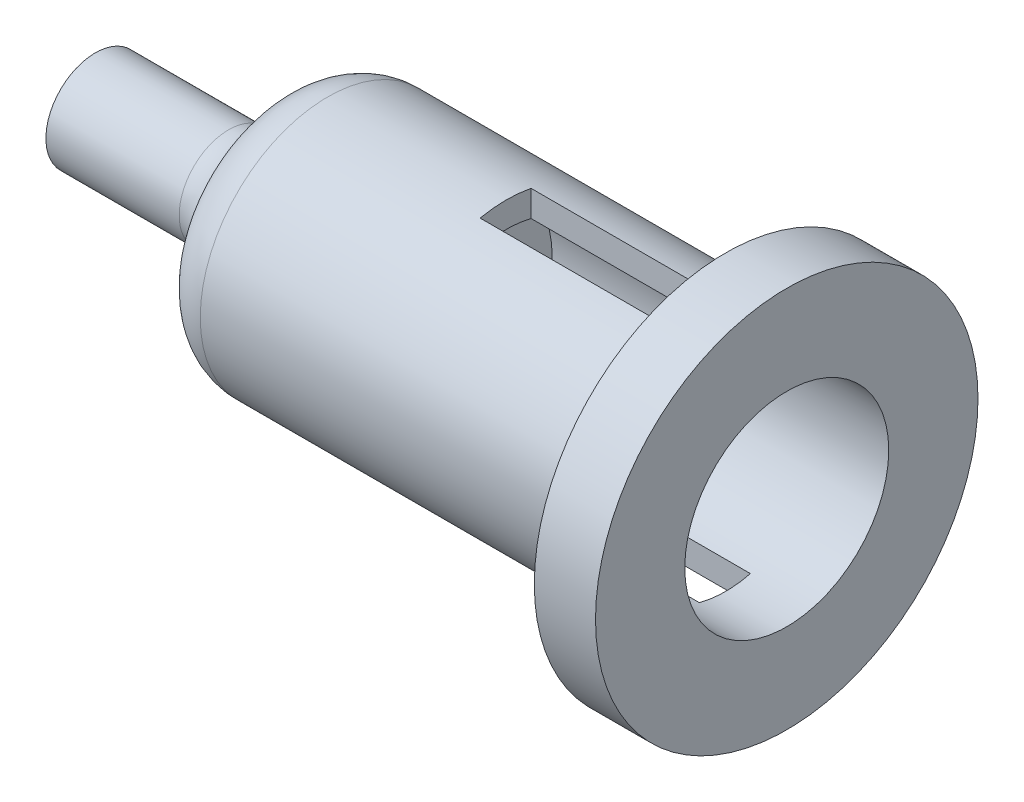
SolidWorks part; units mm, degrees
ref_plane "Front Plane" through (0, 0, 0) normal (0, 0, 1) x (1, 0, 0)
ref_plane "Top Plane" through (0, 0, 0) normal (0, 1, 0) x (1, 0, 0)
ref_plane "Right Plane" through (0, 0, 0) normal (1, 0, 0) x (0, 0, -1)
sketch "Sketch1" plane through (0, 0, 0) normal (0, 1, 0) x (1, 0, 0)
  line L0 (-99.3637, 9.691) -> (-63.789, 9.691)
  line L1 (-63.789, 9.691) -> (-63.789, 25)
  line L2 (-63.789, 25) -> (24.211, 25)
  line L3 (24.211, 25) -> (24.211, 37.5)
  line L4 (24.211, 37.5) -> (36.211, 37.5)
  line L5 (36.211, 37.5) -> (36.211, 20)
  line L6 (36.211, 20) -> (-29.789, 20)
  line L7 (-29.789, 20) -> (-29.789, 0)
  line L8 (-29.789, 0) -> (-99.3637, 0)
  line L9 (-99.3637, 0) -> (-99.3637, 9.691)
  point P2 (30.211, 37.5)
  dimension "D1" = 9.691
  dimension "D2" = 25
  dimension "D3" = 20
  dimension "D4" = 66
  dimension "D5" = 12
  dimension "D6" = 34
  dimension "D7" = 37.5
revolve "Revolve1" add sketch "Sketch1" angle 360 about L8
fillet "Fillet1" radius 10 1 edges at (-63.789, 0, -25)
fillet "Fillet2" radius 10 1 edges at (-63.789, 0, -9.691)
sketch "Sketch2" plane through (0, 0, 0) normal (0, 1, 0) x (1, 0, 0)
  line L1 (-18.789, 4.8733) -> (24.211, 4.8733)
  line L2 (-18.789, 4.8733) -> (-18.789, -5.1267)
  line L3 (-18.789, -5.1267) -> (24.211, -5.1267)
  line L4 (24.211, 4.8733) -> (24.211, -5.1267)
  line L5 (36.211, -37.5) -> (36.211, 37.5) construction
  dimension "D1" = 10
  dimension "D2" = 43
  dimension "D3" = 12
extrude "Cut-Extrude1" cut sketch "Sketch2" against normal through all both and the other way through all
